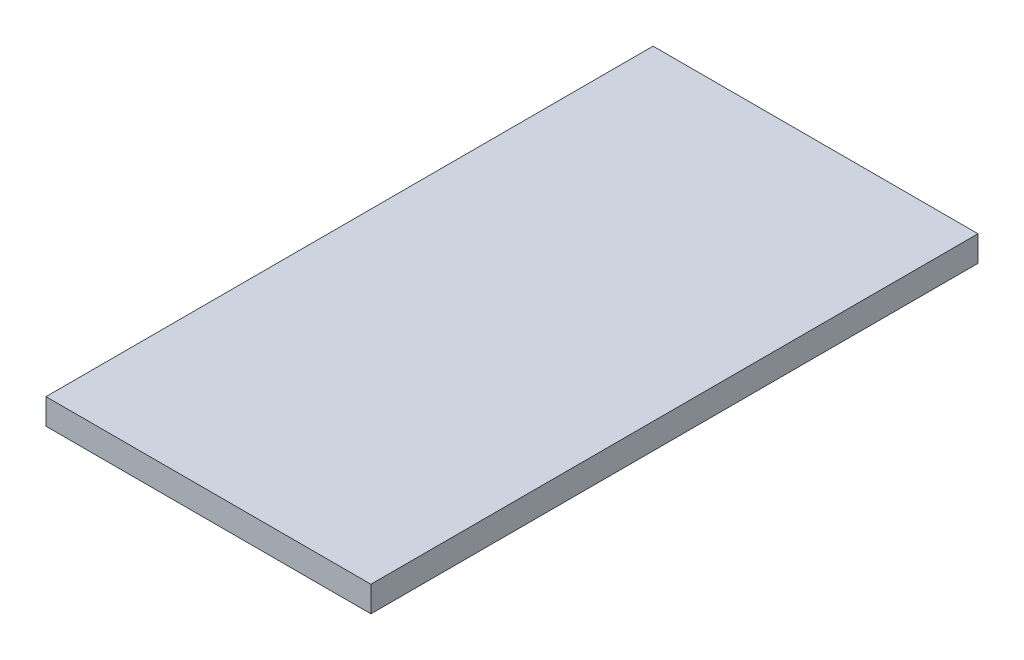
SolidWorks part; units mm, degrees
ref_plane "Alzado" through (0, 0, 0) normal (0, 0, 1) x (1, 0, 0)
ref_plane "Planta" through (0, 0, 0) normal (0, 1, 0) x (1, 0, 0)
ref_plane "Vista lateral" through (0, 0, 0) normal (1, 0, 0) x (0, 0, -1)
sketch "Croquis1" plane through (0, 0, 0) normal (0, 1, 0) x (1, 0, 0)
  line L5 (0, 0) -> (380, 0)
  line L6 (0, 0) -> (0, 710)
  line L7 (0, 710) -> (380, 710)
  line L8 (380, 0) -> (380, 710)
  dimension "D1" = 380
  dimension "D2" = 710
extrude "Saliente-Extruir1" add sketch "Croquis1" along normal blind 30
